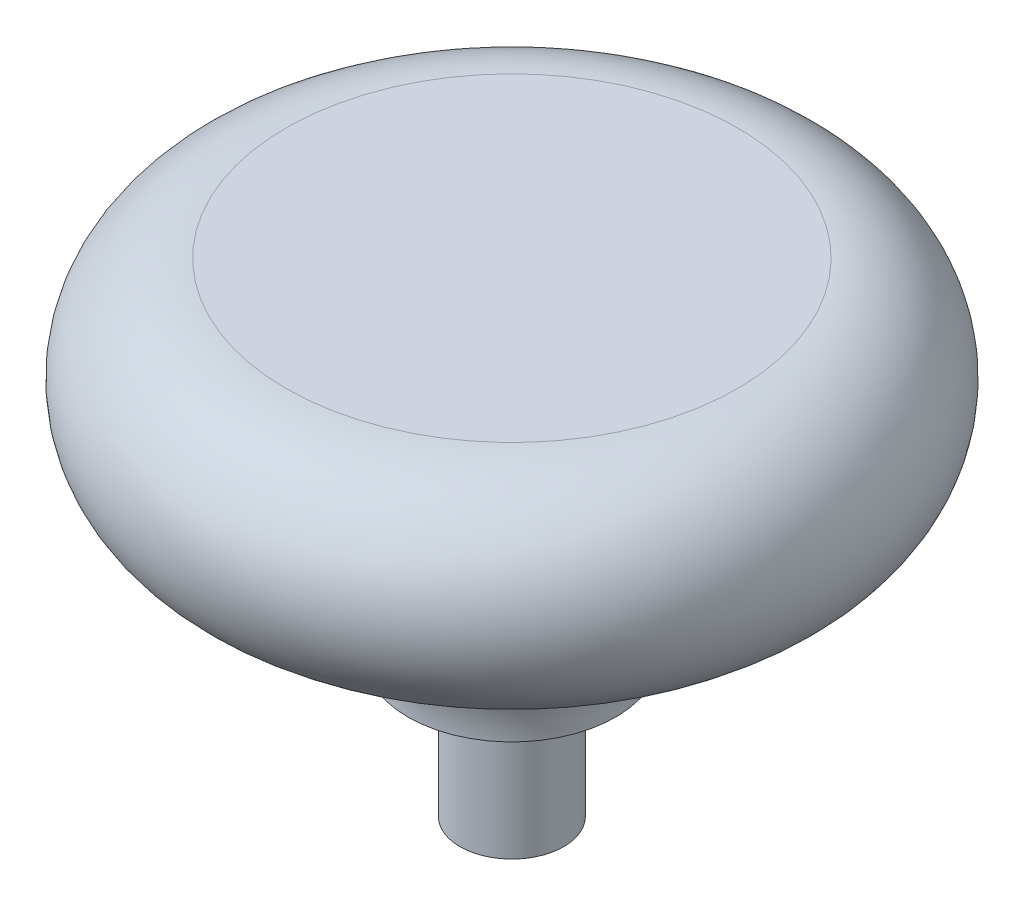
SolidWorks part; units mm, degrees
ref_plane "정면" through (0, 0, 0) normal (0, 0, 1) x (1, 0, 0)
ref_plane "윗면" through (0, 0, 0) normal (0, 1, 0) x (1, 0, 0)
ref_plane "우측면" through (0, 0, 0) normal (1, 0, 0) x (0, 0, -1)
ref_plane "평면1" through (0, 0, 0) normal (0, 0, -1) x (-1, 0, 0)
sketch "스케치1" plane through (0, 0, 0) normal (0, 0, -1) x (-1, 0, 0)
  line L0 (-2.3876, 0) -> (0, 0)
  line L1 (0, 0) -> (0, 22.225)
  line L2 (0, 22.225) -> (-10.3739, 22.225)
  line L3 (-4.7752, 6.35) -> (-2.3876, 6.35)
  line L4 (-2.3876, 6.35) -> (-2.3876, 0)
  line L5 (0, 0) -> (0, 22.225) construction
  arc A0 (-10.3739, 22.225) -> (-10.6964, 12.6855) centre (-10.3739, 17.4498) ccw
  arc A1 (-10.6964, 12.6855) -> (-4.7752, 6.35) centre (-11.1252, 6.35) cw
revolve "회전1" add sketch "스케치1" angle 360 about L5
